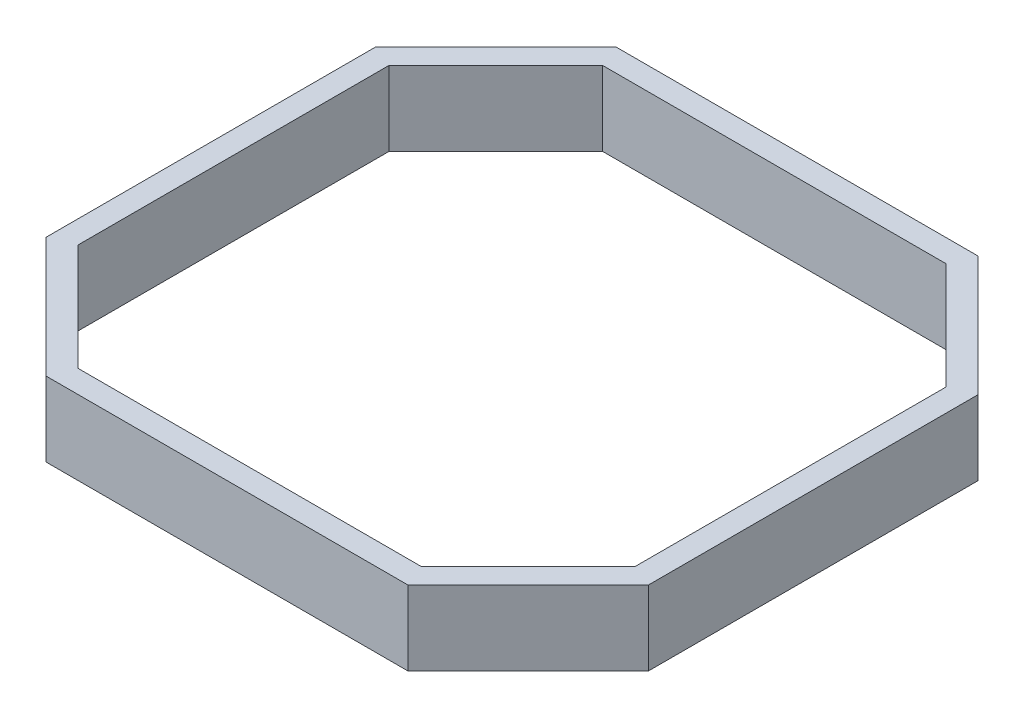
SolidWorks part; units mm, degrees
material "Copper"
ref_plane "Front Plane" through (0, 0, 0) normal (0, 0, 1) x (1, 0, 0)
ref_plane "Top Plane" through (0, 0, 0) normal (0, 1, 0) x (1, 0, 0)
ref_plane "Right Plane" through (0, 0, 0) normal (1, 0, 0) x (0, 0, -1)
sketch "Sketch1" plane through (0, 0, 0) normal (0, 1, 0) x (1, 0, 0)
  line L0 (-43, 24) -> (-26.5, 40.5)
  line L1 (-26.5, -40.5) -> (26.5, -40.5)
  line L2 (-43, -24) -> (-43, 24)
  line L3 (-26.5, 40.5) -> (26.5, 40.5)
  line L4 (43, -24) -> (43, 24)
  line L5 (0, 0) -> (0, -40.5) construction
  line L6 (0, 0) -> (-43, 0) construction
  line L7 (-43, -24) -> (-26.5, -40.5)
  line L8 (26.5, -40.5) -> (43, -24)
  line L9 (26.5, 40.5) -> (43, 24)
  line L10 (0, 0) -> (0, 40.5) construction
  line L11 (0, 0) -> (43, 0) construction
  line L12 (-46.5, 25.4497) -> (-27.9497, 44)
  line L13 (-27.9497, 44) -> (27.9497, 44)
  line L14 (27.9497, 44) -> (46.5, 25.4497)
  line L15 (46.5, -25.4497) -> (46.5, 25.4497)
  line L16 (27.9497, -44) -> (46.5, -25.4497)
  line L17 (-27.9497, -44) -> (27.9497, -44)
  line L18 (-46.5, -25.4497) -> (-27.9497, -44)
  line L19 (-46.5, -25.4497) -> (-46.5, 25.4497)
  point P0 (0, 0)
  dimension "D1" = 86
  dimension "D2" = 81
  dimension "D3" = 48
  dimension "D4" = 53
  dimension "D5" = 3.5
extrude "Boss-Extrude1" add sketch "Sketch1" along normal blind 11.5
